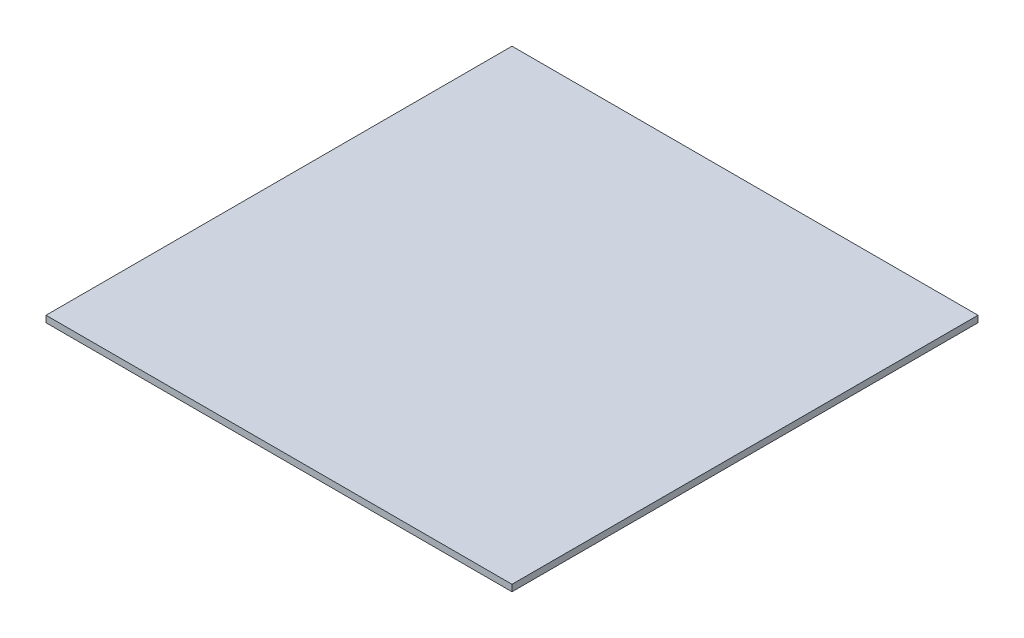
SolidWorks part; units mm, degrees
ref_plane "Plano frontal" through (0, 0, 0) normal (0, 0, 1) x (1, 0, 0)
ref_plane "Plano superior" through (0, 0, 0) normal (0, 1, 0) x (1, 0, 0)
ref_plane "Plano direito" through (0, 0, 0) normal (1, 0, 0) x (0, 0, -1)
sketch "Esboço1" plane through (0, 0, 0) normal (0, 1, 0) x (1, 0, 0)
  line L1 (0, 0) -> (214, 0)
  line L2 (0, 0) -> (0, 214)
  line L3 (0, 214) -> (214, 214)
  line L4 (214, 0) -> (214, 214)
  dimension "D1" = 214
  dimension "D2" = 214
extrude "Ressalto-extrusão1" add sketch "Esboço1" along normal blind 3
